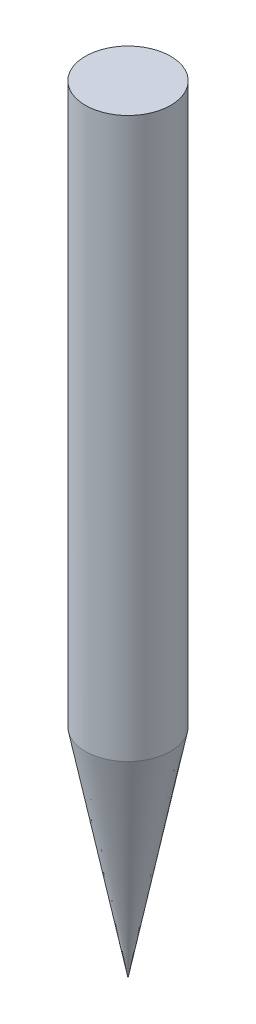
SolidWorks part; units mm, degrees
ref_plane "Front Plane" through (0, 0, 0) normal (0, 0, 1) x (1, 0, 0)
ref_plane "Top Plane" through (0, 0, 0) normal (0, 1, 0) x (1, 0, 0)
ref_plane "Right Plane" through (0, 0, 0) normal (1, 0, 0) x (0, 0, -1)
sketch "Sketch1" plane through (0, 0, 0) normal (0, 0, 1) x (1, 0, 0)
  line L0 (0, -1000) -> (0, 49000) construction
  line L1 (0, 62.5) -> (-3.425, 62.5)
  line L2 (-3.425, 62.5) -> (-3.425, 17.5)
  line L3 (-3.425, 17.5) -> (0, 0)
  line L4 (0, 0) -> (0, 62.5)
  dimension "D1" = 6.85
  dimension "D2" = 45
  dimension "D3" = 17.5
revolve "Revolve1" add sketch "Sketch1" angle 360 about L0
